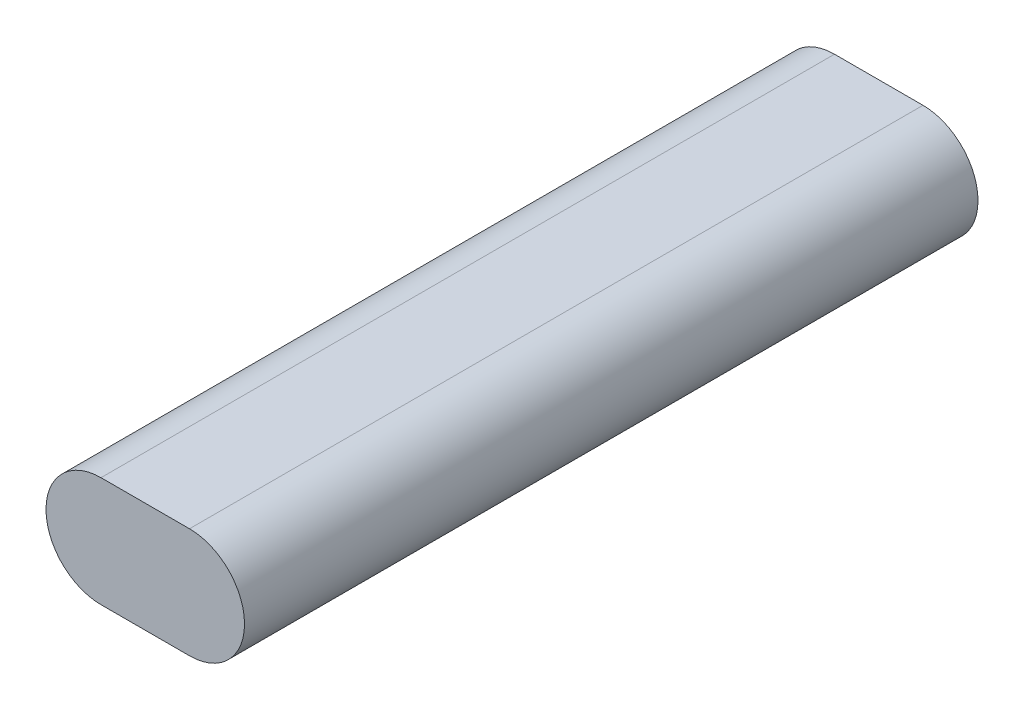
SolidWorks part; units mm, degrees
material "6061-T6 (SS)"
ref_plane "Front" through (0, 0, 0) normal (0, 0, 1) x (1, 0, 0)
ref_plane "Top" through (0, 0, 0) normal (0, 1, 0) x (1, 0, 0)
ref_plane "Right" through (0, 0, 0) normal (1, 0, 0) x (0, 0, -1)
sketch "Sketch1" plane through (0, 0, 0) normal (0, 0, 1) x (1, 0, 0)
  line L0 (-6.575, 0) -> (6.575, 0) construction
  line L1 (-6.575, 8.175) -> (6.575, 8.175)
  line L2 (-6.575, -8.175) -> (6.575, -8.175)
  arc A0 (-6.575, 8.175) -> (-6.575, -8.175) centre (-6.575, 0) ccw
  arc A1 (6.575, -8.175) -> (6.575, 8.175) centre (6.575, 0) ccw
  point P2 (0, 0)
  dimension "D2" = 29.5
  dimension "D1" = 16.35
extrude "Boss-Extrude1" add sketch "Sketch1" along normal blind 109
